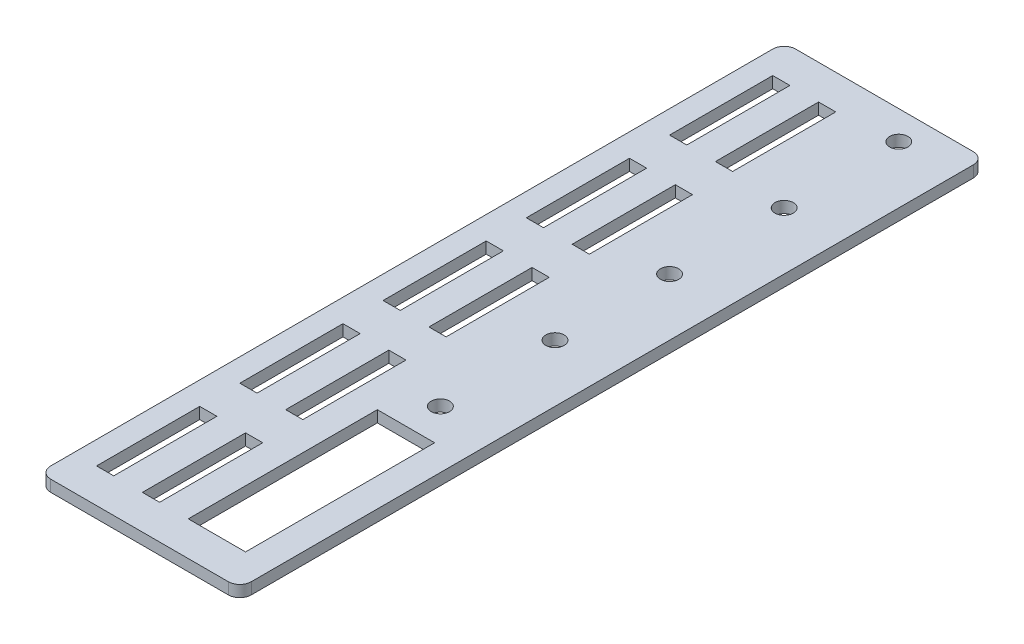
SolidWorks part; units mm, degrees
material "碳板"
ref_plane "前视基准面" through (0, 0, 0) normal (0, 0, 1) x (1, 0, 0)
ref_plane "上视基准面" through (0, 0, 0) normal (0, 1, 0) x (1, 0, 0)
ref_plane "右视基准面" through (0, 0, 0) normal (1, 0, 0) x (0, 0, -1)
sketch "草图1" plane through (0, 0, 0) normal (0, 1, 0) x (1, 0, 0)
  line L0 (0, 134.2434) -> (0, -106.1513) construction
  line L1 (-128.4868, 0) -> (116.5132, 0) construction
  line L2 (-10, 60) -> (-10, 40) construction
  line L3 (-35, 65) -> (0, 65)
  line L4 (-35, 65) -> (-35, -65)
  line L5 (-35, -65) -> (0, -65)
  line L6 (0, 65) -> (0, -65)
  line L7 (-35, 65) -> (0, -65) construction
  line L8 (-35, -65) -> (0, 65) construction
  line L9 (-31, 59) -> (-31, 41)
  line L10 (-23, 59) -> (-20, 59)
  line L11 (-23, 59) -> (-23, 41)
  line L12 (-23, 41) -> (-20, 41)
  line L13 (-20, 59) -> (-20, 41)
  line L14 (-23, 59) -> (-20, 41) construction
  line L15 (-23, 41) -> (-20, 59) construction
  line L16 (-31, 59) -> (-28, 59)
  line L17 (-28, 59) -> (-28, 41)
  line L18 (-31, 41) -> (-28, 41)
  line L19 (-31, 34) -> (-31, 16)
  line L20 (-31, 34) -> (-28, 34)
  line L21 (-28, 34) -> (-28, 16)
  line L22 (-31, 16) -> (-28, 16)
  line L23 (-31, 9) -> (-31, -9)
  line L24 (-31, 9) -> (-28, 9)
  line L25 (-28, 9) -> (-28, -9)
  line L26 (-31, -9) -> (-28, -9)
  line L27 (-31, -16) -> (-31, -34)
  line L28 (-31, -16) -> (-28, -16)
  line L29 (-28, -16) -> (-28, -34)
  line L30 (-31, -34) -> (-28, -34)
  line L31 (-31, -41) -> (-31, -59)
  line L32 (-31, -41) -> (-28, -41)
  line L33 (-28, -41) -> (-28, -59)
  line L34 (-31, -59) -> (-28, -59)
  line L35 (-23, 34) -> (-23, 16)
  line L36 (-23, 34) -> (-20, 34)
  line L37 (-20, 34) -> (-20, 16)
  line L38 (-23, 16) -> (-20, 16)
  line L39 (-23, 9) -> (-23, -9)
  line L40 (-23, 9) -> (-20, 9)
  line L41 (-20, 9) -> (-20, -9)
  line L42 (-23, -9) -> (-20, -9)
  line L43 (-23, -16) -> (-23, -34)
  line L44 (-23, -16) -> (-20, -16)
  line L45 (-20, -16) -> (-20, -34)
  line L46 (-23, -34) -> (-20, -34)
  line L47 (-23, -41) -> (-23, -59)
  line L48 (-23, -41) -> (-20, -41)
  line L49 (-20, -41) -> (-20, -59)
  line L50 (-23, -59) -> (-20, -59)
  line L51 (-23, 59) -> (-31, 59) construction
  line L52 (-23, 59) -> (-23, 34) construction
  line L54 (-15, -26) -> (-5, -26)
  line L55 (-15, -26) -> (-15, -59)
  line L56 (-15, -59) -> (-5, -59)
  line L57 (-5, -26) -> (-5, -59)
  line L58 (-15, -26) -> (-5, -59) construction
  line L59 (-15, -59) -> (-5, -26) construction
  circle A0 centre (-10, 60) radius 1.6
  circle A2 centre (-10, 40) radius 1.6
  circle A3 centre (-10, 20) radius 1.6
  circle A4 centre (-10, 0) radius 1.6
  circle A5 centre (-10, -20) radius 1.6
  point P5 (-17.5, 0)
  point P12 (-21.5, 50)
  point P28 (0, 0)
  point P29 (-10, -42.5)
  point P72 (0, 0)
  dimension "D3" = 3.2
  dimension "D5" = 5
  dimension "D1" = 35
  dimension "D2" = 130
  dimension "D4" = 5
  dimension "D6" = 10
  dimension "D7" = 20
  dimension "D8" = 20
  dimension "D9" = 3
  dimension "D10" = 6
  dimension "D11" = 18
  dimension "D14" = 8
  dimension "D15" = 25
  dimension "D16" = 10
  dimension "D17" = 6
  dimension "D12" = 2
  dimension "D13" = 5
extrude "凸台-拉伸1" add sketch "草图1" along normal blind 2
fillet "圆角1" radius 2 4 edges at (-35, 1, 65) (-35, 1, -65) (0, 1, -65) (0, 1, 65)
